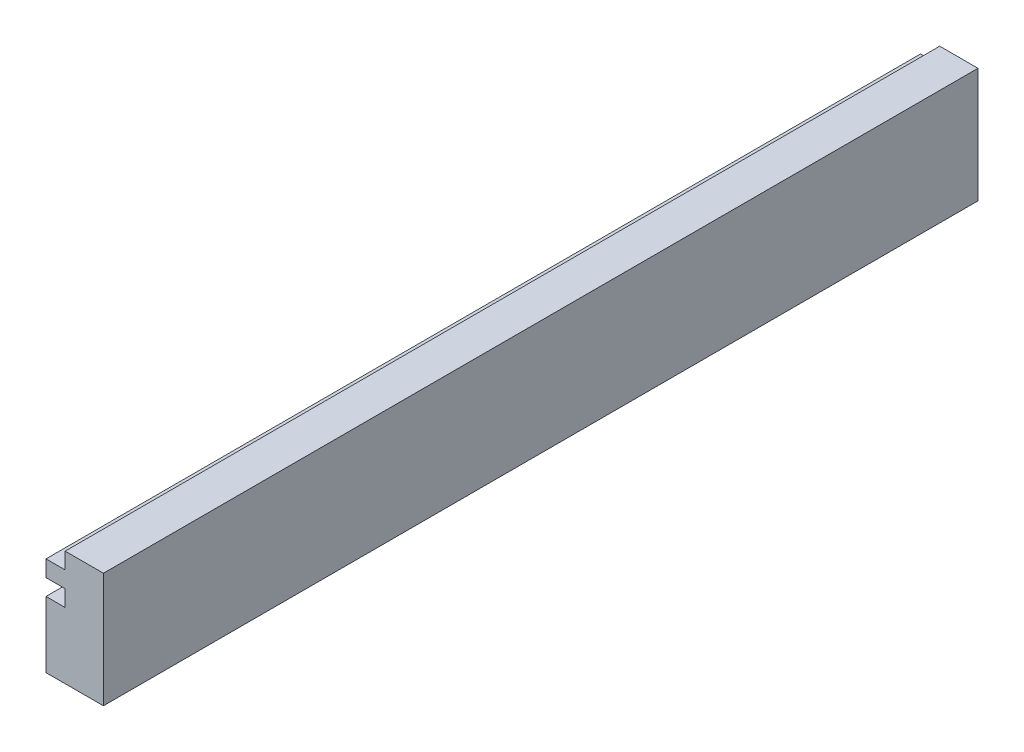
SolidWorks part; units mm, degrees
ref_plane "Front Plane" through (0, 0, 0) normal (0, 0, 1) x (1, 0, 0)
ref_plane "Top Plane" through (0, 0, 0) normal (0, 1, 0) x (1, 0, 0)
ref_plane "Right Plane" through (0, 0, 0) normal (1, 0, 0) x (0, 0, -1)
sketch "Sketch1" plane through (0, 0, 0) normal (0, 0, 1) x (1, 0, 0)
  line L1 (0, 0) -> (30, 0)
  line L2 (0, 0) -> (0, 60)
  line L3 (0, 60) -> (30, 60)
  line L4 (30, 0) -> (30, 60)
  dimension "D1" = 30
  dimension "D2" = 60
extrude "Boss-Extrude1" add sketch "Sketch1" along normal blind 457
sketch "Sketch2" plane through (0, 0, 457) normal (0, 0, 1) x (1, 0, 0)
  line L1 (0, 60) -> (10, 60)
  line L2 (0, 60) -> (0, 51.5)
  line L3 (0, 51.5) -> (10, 51.5)
  line L4 (10, 60) -> (10, 51.5)
  line L9 (0, 43) -> (0, 34.5)
  line L10 (0, 43) -> (10, 43)
  line L11 (10, 43) -> (10, 34.5)
  line L12 (0, 34.5) -> (10, 34.5)
  line M1 (0, 60) -> (0, 0)
  dimension "D1" = 10
  dimension "D2" = 8.5
  dimension "D3" = 2
  dimension "D4" = 8.5
extrude "Cut-Extrude1" cut sketch "Sketch2" against normal blind 500 contours L12 L11 L10 M1 | L2 L1 L4 L3
sketch "Sketch3" plane through (0, 0, 0) normal (0, 0, -1) x (-1, 0, 0)
  line L0 (0, 34.5) -> (0, 0) construction
  line L1 (0, 26) -> (-10, 26)
  line L2 (0, 26) -> (0, 17.5)
  line L3 (0, 17.5) -> (-10, 17.5)
  line L4 (-10, 26) -> (-10, 17.5)
  line L5 (0, 34.5) -> (-10, 34.5) construction
  dimension "D1" = 10
  dimension "D2" = 8.5
  dimension "D3" = 8.5
extrude "Cut-Extrude2" cut sketch "Sketch3" against normal blind 42.89
